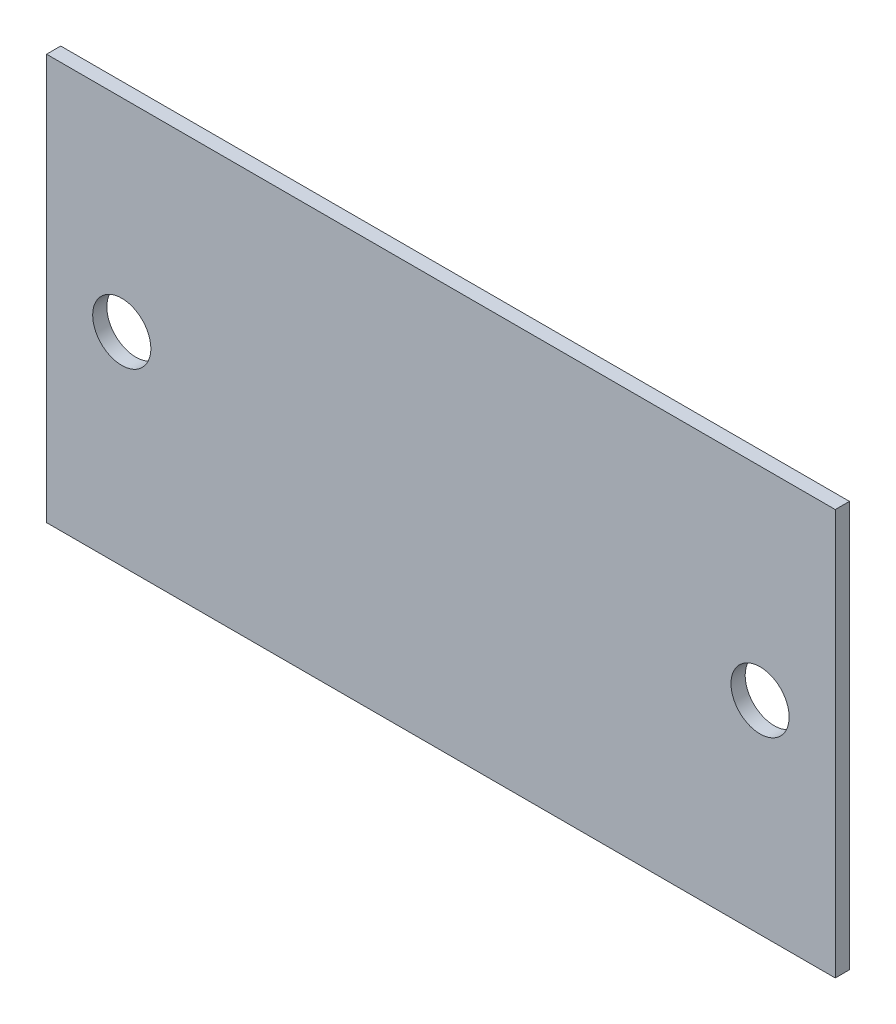
SolidWorks part; units mm, degrees
ref_plane "Ebene vorne" through (0, 0, 0) normal (0, 0, 1) x (1, 0, 0)
ref_plane "Ebene oben" through (0, 0, 0) normal (0, 1, 0) x (1, 0, 0)
ref_plane "Ebene rechts" through (0, 0, 0) normal (1, 0, 0) x (0, 0, -1)
sketch "Skizze1" plane through (0, 0, -37) normal (0, 0, -1) x (-1, 0, 0)
  line L17 (-27.8, 122.1728) -> (-27.8, 93.5728)
  line L18 (-27.8, 93.5728) -> (27.8, 93.5728)
  line L19 (27.8, 93.5728) -> (27.8, 122.1728)
  line L21 (-27.8, 122.1728) -> (-27.8, 93.5728)
  line L22 (-27.8, 93.5728) -> (27.8, 93.5728)
  line L23 (27.8, 93.5728) -> (27.8, 122.1728)
  line L37 (27.8, 122.1728) -> (-27.8, 122.1728)
  line L38 (27.8, 122.1728) -> (-27.8, 122.1728)
  circle A0 centre (-22.5, 107.8728) radius 2.05 construction
  circle A1 centre (-22.5, 107.8728) radius 2.05
  circle A2 centre (22.5, 107.8728) radius 2.05 construction
  circle A3 centre (22.5, 107.8728) radius 2.05
  dimension "D1" = 0.2
extrude "Aufsatz-Linear austragen1" add sketch "Skizze1" along normal blind 1
